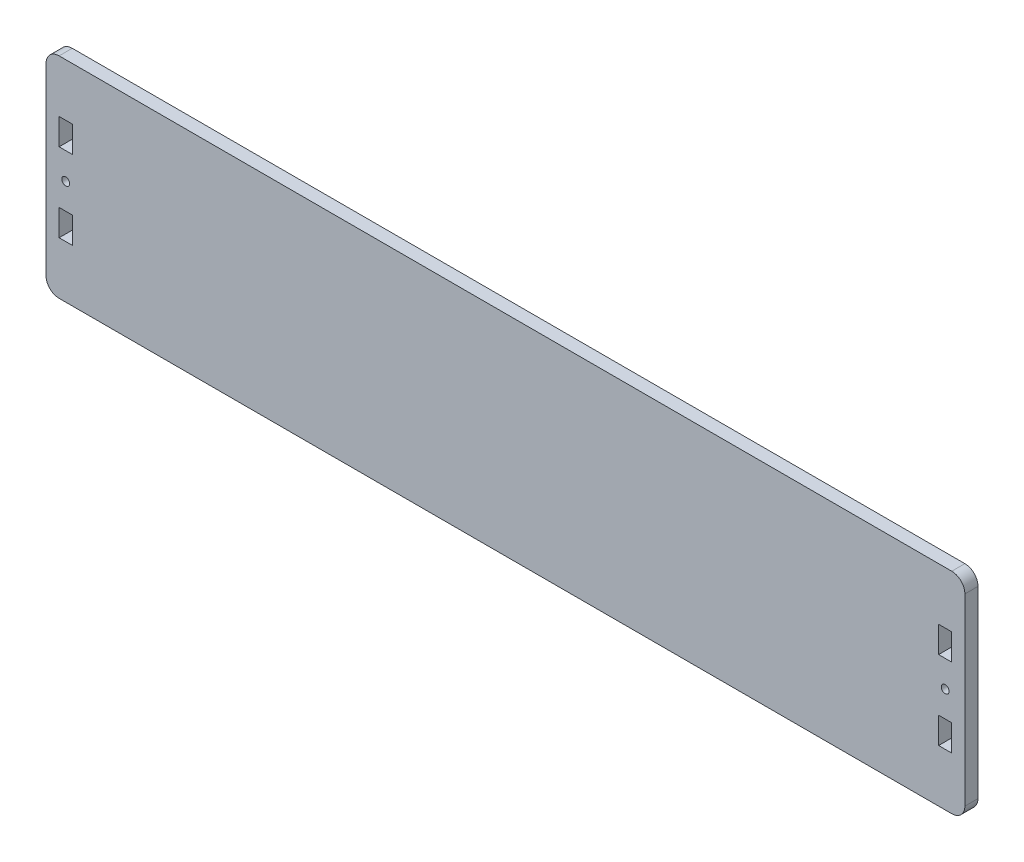
SolidWorks part; units mm, degrees
ref_plane "Front Plane" through (0, 0, 0) normal (0, 0, 1) x (1, 0, 0)
ref_plane "Top Plane" through (0, 0, 0) normal (0, 1, 0) x (1, 0, 0)
ref_plane "Right Plane" through (0, 0, 0) normal (1, 0, 0) x (0, 0, -1)
sketch "Esquisse1" plane through (0, 0, 0) normal (0, 0, 1) x (1, 0, 0)
  line L0 (-89.1308, 56.2835) -> (-89.1308, -45.1751) construction
  line L1 (-96.6308, 52.4586) -> (253.3692, 52.4586)
  line L2 (-96.6308, 52.4586) -> (-96.6308, -27.5414)
  line L3 (-96.6308, -27.5414) -> (253.3692, -27.5414)
  line L4 (253.3692, 52.4586) -> (253.3692, -27.5414)
  line L5 (78.3692, 76.6425) -> (78.3692, -59.8412) construction
  line L6 (245.8692, 56.2835) -> (245.8692, -45.1751) construction
  line L7 (-91.6308, 32.4586) -> (-86.6308, 32.4586)
  line L8 (-91.6308, 32.4586) -> (-91.6308, 22.4586)
  line L9 (-91.6308, 22.4586) -> (-86.6308, 22.4586)
  line L10 (-86.6308, 32.4586) -> (-86.6308, 22.4586)
  line L11 (-91.6308, 2.4586) -> (-86.6308, 2.4586)
  line L12 (-91.6308, 2.4586) -> (-91.6308, -7.5414)
  line L13 (-91.6308, -7.5414) -> (-86.6308, -7.5414)
  line L14 (-86.6308, 2.4586) -> (-86.6308, -7.5414)
  line L15 (243.3692, 2.4586) -> (243.3692, -7.5414)
  line L16 (248.3692, -7.5414) -> (243.3692, -7.5414)
  line L17 (248.3692, 2.4586) -> (248.3692, -7.5414)
  line L18 (248.3692, 2.4586) -> (243.3692, 2.4586)
  line L19 (243.3692, 32.4586) -> (243.3692, 22.4586)
  line L20 (248.3692, 22.4586) -> (243.3692, 22.4586)
  line L21 (248.3692, 32.4586) -> (248.3692, 22.4586)
  line L22 (248.3692, 32.4586) -> (243.3692, 32.4586)
  circle A0 centre (-89.1308, 12.3041) radius 1.5
  circle A1 centre (245.8692, 12.3041) radius 1.5
  point P30 (78.3692, 52.4586)
  point P31 (-86.7184, 12.3041)
  point P32 (-89.1308, -7.5414)
  dimension "D7" = 5
  dimension "D1" = 80
  dimension "D2" = 350
  dimension "D3" = 10
  dimension "D4" = 20
  dimension "D5" = 10
  dimension "D6" = 20
  dimension "D8" = 5
extrude "Boss.-Extru.1" add sketch "Esquisse1" along normal blind 5
fillet "Congé1" radius 5 4 edges at (253.3692, 52.4586, 2.5) (253.3692, -27.5414, 2.5) (-96.6308, -27.5414, 2.5) (-96.6308, 52.4586, 2.5)
